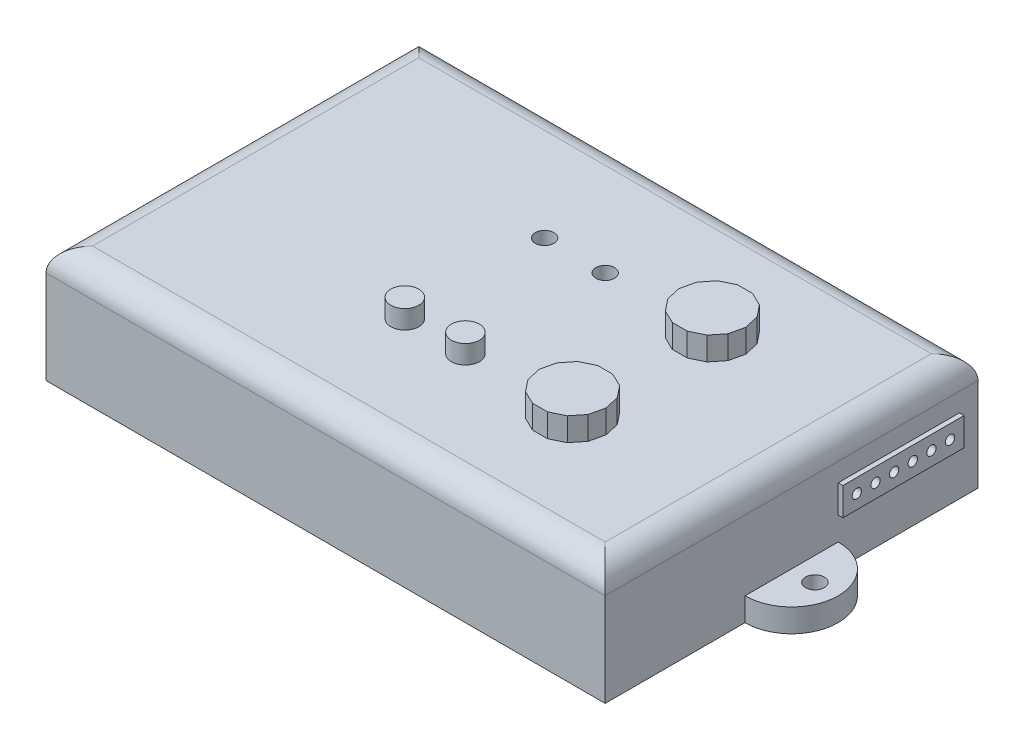
SolidWorks part; units mm, degrees
ref_plane "Front Plane" through (0, 0, 0) normal (0, 0, 1) x (1, 0, 0)
ref_plane "Top Plane" through (0, 0, 0) normal (0, 1, 0) x (1, 0, 0)
ref_plane "Right Plane" through (0, 0, 0) normal (1, 0, 0) x (0, 0, -1)
sketch "Sketch2" plane through (0, 0, 0) normal (0, 1, 0) x (1, 0, 0)
  line L0 (0, 50) -> (0, 30)
  line L1 (0, 0) -> (120, 0)
  line L2 (0, 0) -> (0, 80)
  line L3 (0, 80) -> (120, 80)
  line L4 (120, 0) -> (120, 80)
  line L5 (120, 50) -> (120, 30)
  arc A0 (0, 30) -> (0, 50) centre (0, 40) cw
  arc A1 (120, 50) -> (120, 30) centre (120, 40) cw
  point P11 (130, 40)
  dimension "D4" = 10
  dimension "D1" = 120
  dimension "D2" = 80
  dimension "D3" = 10
extrude "Boss-Extrude2" add sketch "Sketch2" along normal blind 20 contours L1 L4 L3 L2 L0 | A0 L0 | A1 L4
sketch "Sketch3" plane through (0, 20, 0) normal (0, 1, 0) x (1, 0, 0)
  line L0 (0, 50) -> (0, 30)
  line L1 (120, 50) -> (120, 30)
  arc A1 (0, 50) -> (0, 30) centre (0, 40) ccw
  arc A2 (0, 50) -> (0, 30) centre (0, 40) ccw construction
  arc A3 (120, 30) -> (120, 50) centre (120, 40) ccw
extrude "Cut-Extrude1" cut sketch "Sketch3" against normal blind 15
sketch "Sketch4" plane through (0, 20, 0) normal (0, 1, 0) x (1, 0, 0)
  line L0 (-10, 40) -> (130, 40) construction
  line L1 (60, 80) -> (60, 0) construction
  line L2 (0, 80) -> (120, 80) construction
  line L3 (0, 0) -> (120, 0) construction
  line L4 (0, 0) -> (0, 80) construction
  line L5 (117, 3) -> (3, 3)
  line L6 (117, 3) -> (117, 77)
  line L7 (117, 77) -> (3, 77)
  line L8 (3, 3) -> (3, 77)
  line L9 (117, 3) -> (3, 77) construction
  line L10 (117, 77) -> (3, 3) construction
  arc A0 (0, 50) -> (0, 30) centre (0, 40) ccw construction
  arc A1 (120, 30) -> (120, 50) centre (120, 40) ccw construction
  point P14 (60, 40)
  dimension "D1" = 3
  dimension "D2" = 3
extrude "Cut-Extrude2" cut sketch "Sketch4" against normal blind 15
sketch "Sketch5" plane through (0, 0, 0) normal (0, -1, 0) x (1, 0, 0)
  line L0 (130, -40) -> (-10, -40) construction
  circle A0 centre (-5, -40) radius 2
  arc A1 (120, -50) -> (120, -30) centre (120, -40) ccw construction
  arc A2 (0, -30) -> (0, -50) centre (0, -40) ccw construction
  circle A3 centre (125, -40) radius 2
  dimension "D1" = 5
  dimension "D2" = 4
  dimension "D3" = 4
  dimension "D4" = 5
extrude "Cut-Extrude3" cut sketch "Sketch5" against normal through all
sketch "Sketch8" plane through (120, 0, 0) normal (1, 0, 0) x (0, 0, -1)
  line L0 (80, 20) -> (80, 0) construction
  line L1 (50, 10) -> (76, 10)
  line L2 (50, 10) -> (50, 16)
  line L3 (50, 16) -> (76, 16)
  line L4 (76, 10) -> (76, 16)
  line L5 (50, 0) -> (80, 0) construction
  dimension "D1" = 26
  dimension "D2" = 6
  dimension "D3" = 4
  dimension "D4" = 10
extrude "Boss-Extrude3" add sketch "Sketch8" along normal blind 1 and the other way blind 6
sketch "Sketch6" plane through (120, 0, 0) normal (1, 0, 0) x (0, 0, -1)
  line L0 (56.6884, 15.8489) -> (78.9116, 15.8489) construction
  line L1 (78.9116, 15.8489) -> (78.9116, 10.7333) construction
  line L2 (78.9116, 10.7333) -> (56.6884, 10.7333) construction
  line L3 (56.6884, 10.7333) -> (56.6884, 15.8489) construction
  line L4 (50, 0) -> (80, 0) construction
  line L5 (80, 20) -> (80, 0) construction
  circle A0 centre (73, 13) radius 1
  circle A1 centre (57, 13) radius 1
  circle A2 centre (53, 13) radius 1
  circle A3 centre (65, 13) radius 1
  circle A4 centre (61, 13) radius 1
  circle A5 centre (69, 13) radius 1
  dimension "D1" = 2
  dimension "D5" = 2
  dimension "D6" = 2
  dimension "D2" = 13
  dimension "D3" = 7
  dimension "D4" = 23
  dimension "D7" = 27
  dimension "D8" = 13
  dimension "D9" = 15
  dimension "D10" = 19
  dimension "D11" = 11
extrude "Cut-Extrude4" cut sketch "Sketch6" against normal blind 35 and the other way blind 2
sketch "Sketch10" plane through (0, 5, 0) normal (0, 1, 0) x (1, 0, 0)
  line L0 (117, 77) -> (3, 77) construction
  line L1 (3, 3) -> (117, 3) construction
  line L2 (117, 3) -> (117, 77) construction
  line L3 (3, 77) -> (3, 3) construction
  circle A0 centre (12, 69.7183) radius 2
  circle A1 centre (12, 11) radius 2
  circle A2 centre (103, 69) radius 2
  circle A3 centre (103, 11) radius 2
  dimension "D1" = 4
  dimension "D2" = 4
  dimension "D3" = 4
  dimension "D4" = 4
  dimension "D5" = 8
  dimension "D6" = 8
  dimension "D7" = 14
  dimension "D8" = 9
extrude "Boss-Extrude4" add sketch "Sketch10" along normal blind 15
sketch "Sketch11" plane through (0, 20, 0) normal (0, 1, 0) x (1, 0, 0)
  circle A0 centre (12, 69.7183) radius 1.5
  circle A1 centre (103, 69) radius 1.5
  circle A2 centre (12, 11) radius 1.5
  circle A3 centre (103, 11) radius 1.5
  dimension "D1" = 3
  dimension "D2" = 3
  dimension "D3" = 3
  dimension "D4" = 3
extrude "Cut-Extrude5" cut sketch "Sketch11" against normal blind 15
sketch "Sketch12" plane through (0, 0, 0) normal (-1, 0, 0) x (0, 0, 1)
  line L1 (-80, 20) -> (0, 20)
  line L2 (-80, 20) -> (-80, 25)
  line L3 (-80, 25) -> (0, 25)
  line L4 (0, 20) -> (0, 25)
  dimension "D1" = 5
extrude "Boss-Extrude5" add sketch "Sketch12" against normal blind 120
fillet "Fillet1" radius 5 4 edges at (0, 25, -40) (120, 25, -40) (60, 25, 0) (60, 25, -80)
sketch "Sketch13" plane through (0, 25, 0) normal (0, 1, 0) x (1, 0, 0)
  line L0 (81.531, 58.1153) -> (80.82, 55)
  line L1 (95.18, 55) -> (94.469, 58.1153)
  line L2 (94.469, 58.1153) -> (92.4767, 60.6136)
  line L3 (92.4767, 60.6136) -> (89.5977, 62)
  line L4 (89.5977, 62) -> (86.4023, 62)
  line L5 (86.4023, 62) -> (83.5233, 60.6136)
  line L6 (83.5233, 60.6136) -> (81.531, 58.1153)
  line L7 (80.82, 55) -> (81.531, 51.8847)
  line L8 (81.531, 51.8847) -> (83.5233, 49.3864)
  line L9 (83.5233, 49.3864) -> (86.4023, 48)
  line L10 (86.4023, 48) -> (89.5977, 48)
  line L11 (89.5977, 48) -> (92.4767, 49.3864)
  line L12 (92.4767, 49.3864) -> (94.469, 51.8847)
  line L13 (94.469, 51.8847) -> (95.18, 55)
  line L14 (5, 5) -> (115, 5) construction
  line L15 (95.18, 25) -> (94.469, 28.1153)
  line L16 (94.469, 28.1153) -> (92.4767, 30.6136)
  line L17 (92.4767, 30.6136) -> (89.5977, 32)
  line L18 (89.5977, 32) -> (86.4023, 32)
  line L19 (86.4023, 32) -> (83.5233, 30.6136)
  line L20 (83.5233, 30.6136) -> (81.531, 28.1153)
  line L21 (81.531, 28.1153) -> (80.82, 25)
  line L22 (80.82, 25) -> (81.531, 21.8847)
  line L23 (81.531, 21.8847) -> (83.5233, 19.3864)
  line L24 (83.5233, 19.3864) -> (86.4023, 18)
  line L25 (86.4023, 18) -> (89.5977, 18)
  line L26 (89.5977, 18) -> (92.4767, 19.3864)
  line L27 (92.4767, 19.3864) -> (94.469, 21.8847)
  line L28 (94.469, 21.8847) -> (95.18, 25)
  line L29 (115, 75) -> (5, 75) construction
  line L30 (115, 5) -> (115, 75) construction
  circle A0 centre (88, 55) radius 7 construction
  circle A1 centre (88, 25) radius 7 construction
  dimension "D1" = 7
  dimension "D2" = 7
  dimension "D3" = 20
  dimension "D4" = 20
  dimension "D5" = 27
extrude "Boss-Extrude6" add sketch "Sketch13" along normal blind 5
sketch "Sketch14" plane through (0, 25, 0) normal (0, 1, 0) x (1, 0, 0)
  line L0 (81.531, 21.8847) -> (94.469, 28.1153) construction
  line L1 (94.469, 28.1153) -> (88, 25) construction
  line L2 (88, 25) -> (84.9628, 31.3068) construction
  line L3 (86.4023, 32) -> (83.5233, 30.6136) construction
  line L4 (84.9628, 31.3068) -> (91.0372, 18.6932) construction
  line L5 (89.5977, 18) -> (92.4767, 19.3864) construction
  line L6 (115, 5) -> (115, 75) construction
  line L7 (5, 75) -> (115, 5) construction
  line L8 (115, 5) -> (5, 5) construction
  line L9 (5, 5) -> (115, 75) construction
  line L10 (115, 75) -> (60, 40) construction
  line L11 (60, 40) -> (60, 5) construction
  circle A0 centre (52, 25) radius 3
  circle A1 centre (65, 25) radius 3
  dimension "D1" = 6
  dimension "D2" = 6
  dimension "D3" = 63
  dimension "D4" = 50
extrude "Boss-Extrude7" add sketch "Sketch14" along normal blind 4
sketch "Sketch15" plane through (0, 25, 0) normal (0, 1, 0) x (1, 0, 0)
  line L0 (52, 25) -> (52, 75) construction
  line L1 (115, 75) -> (5, 75) construction
  line L2 (65, 25) -> (65, 75) construction
  line L3 (82.5272, 50.6356) -> (93.4728, 59.3644) construction
  line L4 (81.531, 51.8847) -> (83.5233, 49.3864) construction
  line L5 (94.469, 58.1153) -> (92.4767, 60.6136) construction
  line L6 (93.4728, 59.3644) -> (88, 55) construction
  line L7 (88, 55) -> (5, 55) construction
  line L8 (5, 75) -> (5, 5) construction
  circle A0 centre (52, 55) radius 2
  circle A1 centre (65, 55) radius 2
  dimension "D1" = 4
  dimension "D2" = 4
extrude "Cut-Extrude6" cut sketch "Sketch15" against normal blind 10
sketch "Sketch16" plane through (0, 0, 0) normal (-1, 0, 0) x (0, 0, 1)
  line L0 (-80, 20) -> (-80, 0) construction
  line L1 (-72, 14) -> (-60, 14)
  line L2 (-72, 14) -> (-72, 6)
  line L3 (-72, 6) -> (-60, 6)
  line L4 (-60, 14) -> (-60, 6)
  line L5 (-50, 0) -> (-80, 0) construction
  point P4 (-72, 10)
  dimension "D1" = 8
  dimension "D2" = 12
  dimension "D3" = 8
  dimension "D4" = 6
extrude "Cut-Extrude7" cut sketch "Sketch16" against normal blind 1
sketch "Sketch17" plane through (1, 0, 0) normal (-1, 0, 0) x (0, 0, 1)
  line L0 (-72, 14) -> (-60, 6) construction
  line L1 (-72, 6) -> (-60, 6) construction
  line L2 (-72, 6) -> (-60, 6) construction
  line L3 (-60, 6) -> (-60, 14) construction
  line L4 (-60, 14) -> (-72, 14) construction
  line L5 (-60, 14) -> (-72, 14) construction
  line L6 (-60, 14) -> (-72, 6) construction
  line L8 (-71, 13) -> (-61, 13)
  line L9 (-71, 13) -> (-71, 7)
  line L10 (-71, 7) -> (-61, 7)
  line L11 (-61, 13) -> (-61, 7)
  line L12 (-71, 13) -> (-61, 7) construction
  line L13 (-71, 7) -> (-61, 13) construction
  point P7 (-66, 10)
  dimension "D1" = 10
  dimension "D2" = 6
extrude "Cut-Extrude8" cut sketch "Sketch17" against normal blind 4
